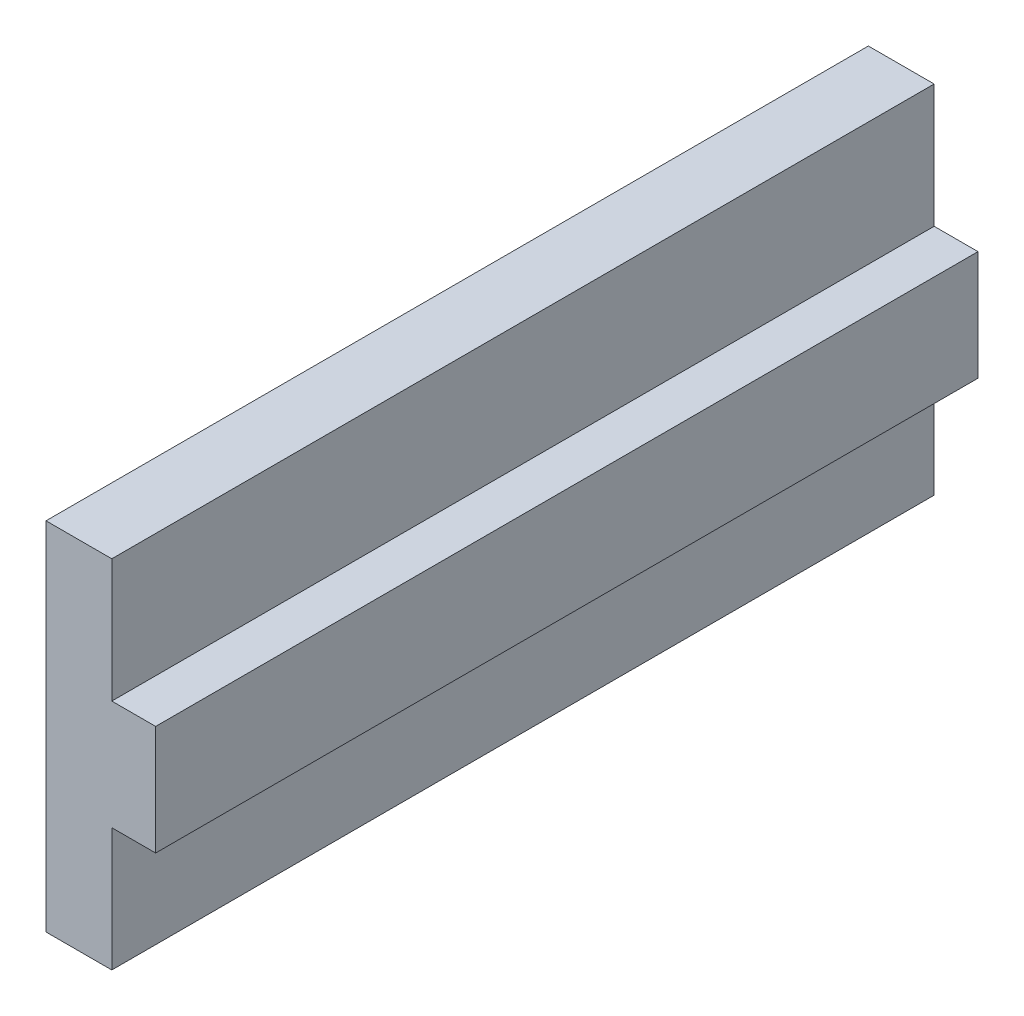
SolidWorks part; units mm, degrees
ref_plane "Front Plane" through (0, 0, 0) normal (0, 0, 1) x (1, 0, 0)
ref_plane "Top Plane" through (0, 0, 0) normal (0, 1, 0) x (1, 0, 0)
ref_plane "Right Plane" through (0, 0, 0) normal (1, 0, 0) x (0, 0, -1)
sketch "Sketch1" plane through (0, 0, 0) normal (0, 0, 1) x (1, 0, 0)
  line L0 (0, 0) -> (0, 20.6248)
  line L1 (0, 20.6248) -> (3.81, 20.6248)
  line L2 (3.81, 20.6248) -> (3.81, 13.4874)
  line L3 (3.81, 13.4874) -> (6.35, 13.4874)
  line L4 (6.35, 13.4874) -> (6.35, 7.1374)
  line L5 (6.35, 7.1374) -> (3.81, 7.1374)
  line L6 (3.81, 7.1374) -> (3.81, 0)
  line L7 (3.81, 0) -> (0, 0)
  dimension "D1" = 20.6248
  dimension "D2" = 3.81
  dimension "D3" = 3.81
  dimension "D4" = 6.35
  dimension "D5" = 2.54
extrude "Boss-Extrude1" add sketch "Sketch1" along normal blind 47.625
